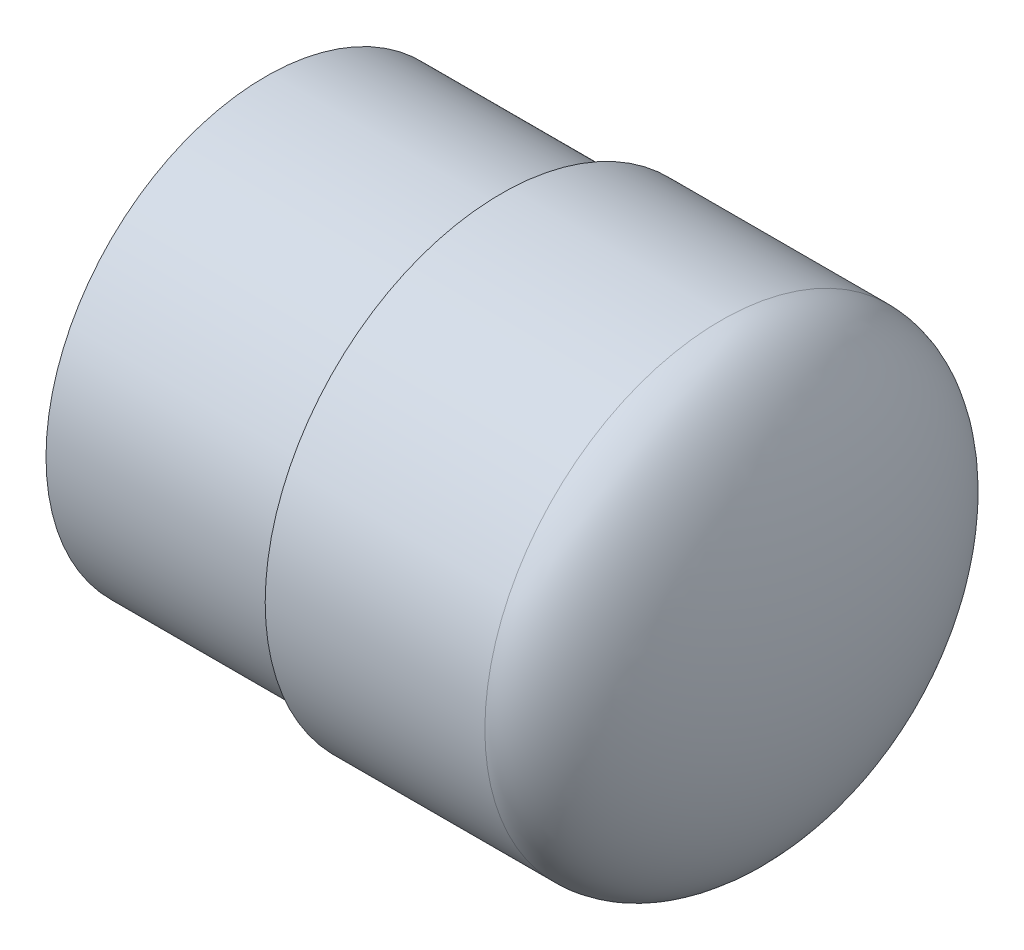
SolidWorks part; units mm, degrees
ref_plane "Front Plane" through (0, 0, 0) normal (0, 0, 1) x (1, 0, 0)
ref_plane "Top Plane" through (0, 0, 0) normal (0, 1, 0) x (1, 0, 0)
ref_plane "Right Plane" through (0, 0, 0) normal (1, 0, 0) x (0, 0, -1)
sketch "Sketch0" plane through (0, 0, 0) normal (0, 0, 1) x (1, 0, 0)
  line L2 (-138.9062, 109.5375) -> (-138.9062, -109.5375) construction
  line L3 (-138.9062, 0) -> (138.9062, 0) construction
  line L14 (130.7275, 101.3587) -> (130.7275, -101.3587) construction
  point P5 (130.7275, 0)
  point P8 (-21.4313, 0)
  dimension "ID" = 202.7174
  dimension "L" = 277.8125
  dimension "C" = 269.6337
  dimension "Pipe OD" = 219.075
  dimension "R" = 8.1788
  dimension "Wall Thickness" = 8.1788
  dimension "Depth" = 117.475
sketch "Sketch1" plane through (0, 0, 0) normal (0, 0, 1) x (1, 0, 0)
  line L0 (-138.9062, -109.5375) -> (-21.4312, -109.5375)
  line L1 (-138.9062, 0) -> (138.9062, 0) construction
  line L2 (-21.4312, -109.5375) -> (-21.4312, -117.7163)
  line L4 (88.1063, -101.3587) -> (-138.9062, -101.3587)
  line L5 (-138.9062, -101.3587) -> (-138.9062, -109.5375)
  line L6 (-138.9062, 109.5375) -> (-138.9062, -109.5375) construction
  line L7 (130.7275, 101.3587) -> (130.7275, -101.3587) construction
  line L8 (-21.4312, -117.7163) -> (88.1063, -117.7163)
  line L9 (130.7275, 0) -> (138.9062, 0)
  ellipse E0 centre (88.1063, 0) end of major axis (88.1063, -101.3587) minor radius 42.6212 (88.1063, -101.3587) -> (130.7275, 0) ccw
  ellipse E1 centre (88.1063, 0) end of major axis (88.1063, 117.7163) minor radius 50.8 (88.1063, -117.7163) -> (138.9062, 0) ccw
  dimension "D1" = 50.8
revolve "Revolve1" add sketch "Sketch1" angle 360 about L1
equation "\"R@Sketch0\" = \"Wall Thickness@Sketch0\""
